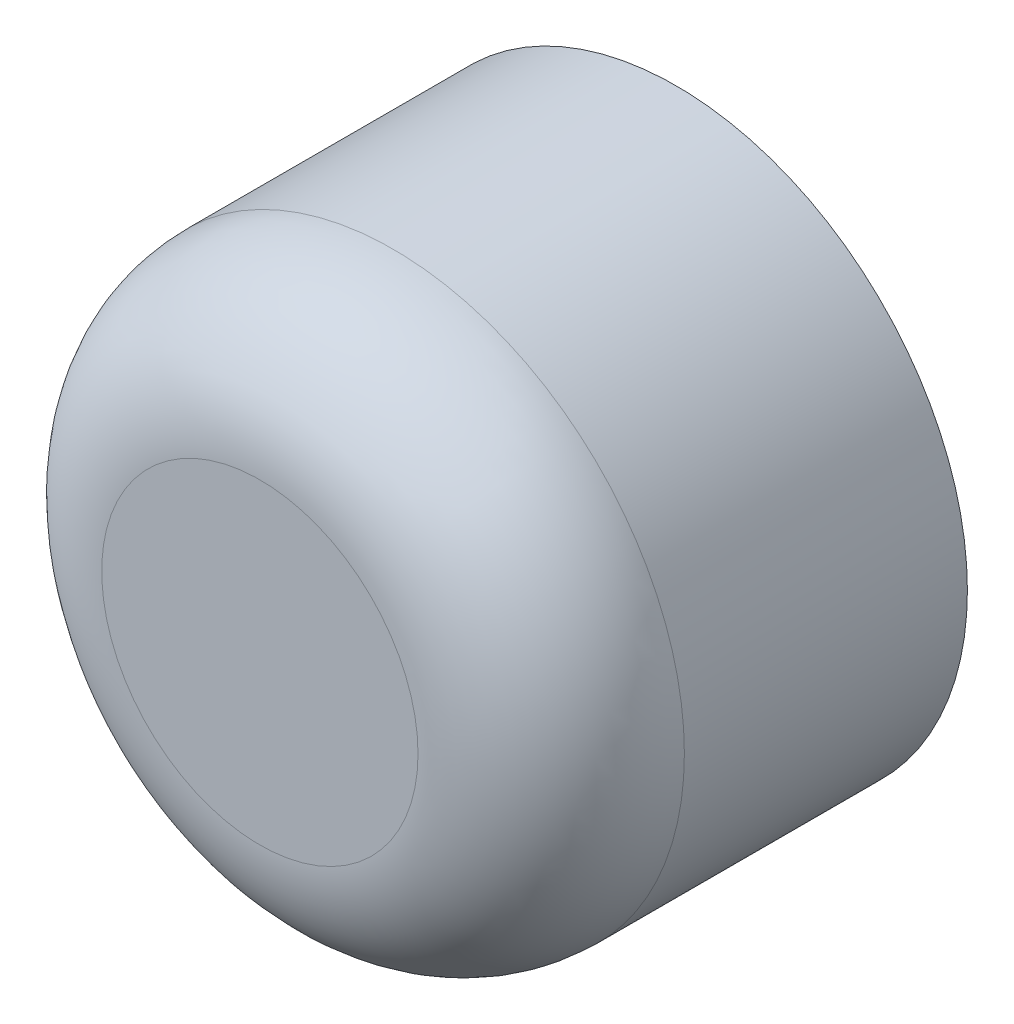
SolidWorks part; units mm, degrees
ref_plane "Front Plane" through (0, 0, 0) normal (0, 0, 1) x (1, 0, 0)
ref_plane "Top Plane" through (0, 0, 0) normal (0, 1, 0) x (1, 0, 0)
ref_plane "Right Plane" through (0, 0, 0) normal (1, 0, 0) x (0, 0, -1)
sketch "Sketch2" plane through (0, 0, 0) normal (0, 0, 1) x (1, 0, 0)
  circle A0 centre (0, 0) radius 12.5
  circle A1 centre (0, 0) radius 17.5
  dimension "D1" = 25
  dimension "D2" = 35
extrude "Boss-Extrude1" add sketch "Sketch2" along normal blind 20
sketch "Sketch3" plane through (0, 0, 20) normal (0, 0, 1) x (1, 0, 0)
  circle A0 centre (0, 0) radius 17.5
  circle A1 centre (0, 0) radius 17.5 construction
extrude "Boss-Extrude2" add sketch "Sketch3" along normal blind 5
fillet "Fillet2" radius 8 1 edges at (17.5, 0, 25)
